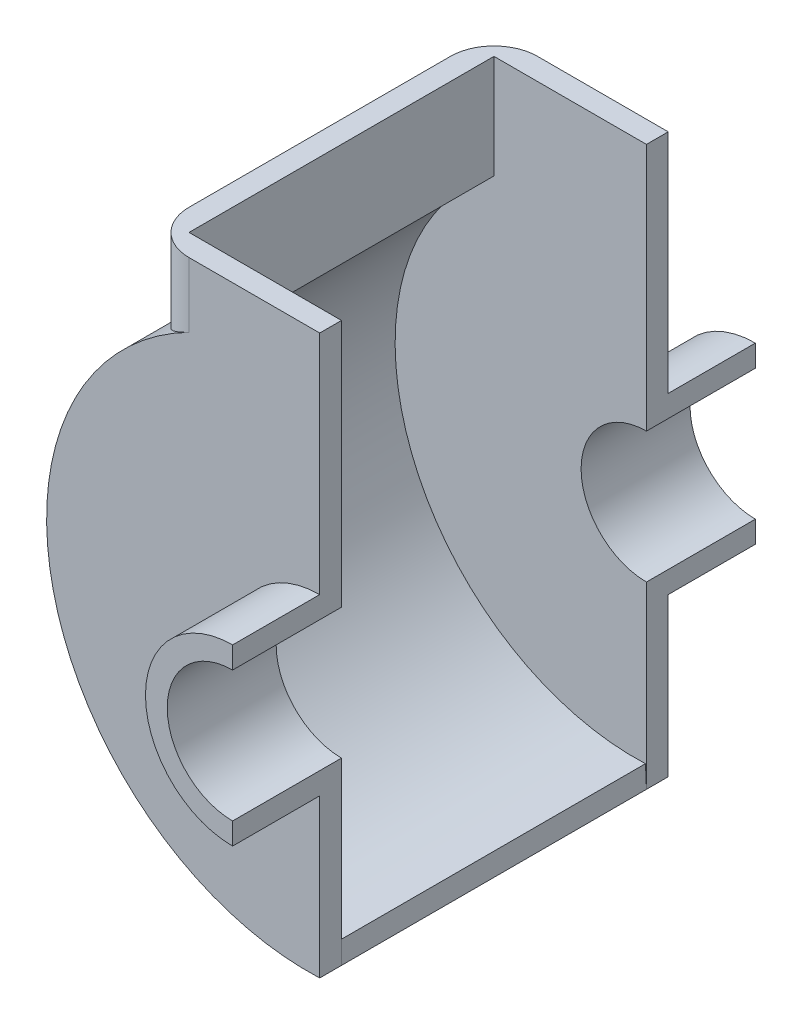
SolidWorks part; units mm, degrees
ref_plane "Płaszczyzna przednia" through (0, 0, 0) normal (0, 0, 1) x (1, 0, 0)
ref_plane "Płaszczyzna górna" through (0, 0, 0) normal (0, 1, 0) x (1, 0, 0)
ref_plane "Płaszczyzna prawa" through (0, 0, 0) normal (1, 0, 0) x (0, 0, -1)
sketch "Szkic1" plane through (0, 0, 0) normal (0, 0, 1) x (1, 0, 0)
  line L0 (0, 15) -> (0, 20)
  line L1 (0, -15) -> (0, -20)
  arc A0 (0, 15) -> (0, -15) centre (0, 0) ccw
  arc A1 (0, 20) -> (0, -20) centre (0, 0) ccw
  dimension "D1" = 30
  dimension "D2" = 40
extrude "Dodanie-wyciągnięcie1" add sketch "Szkic1" along normal blind 25
sketch "Szkic2" plane through (0, 0, 0) normal (0, 0, 1) x (1, 0, 0)
  line L0 (0, 20) -> (0, 72)
  line L1 (0, 72) -> (-40, 72)
  line L2 (-40, 72) -> (-40, 50.7094)
  line L3 (0, -20) -> (0, -56.2205)
  line L6 (0, 15) -> (0, 20)
  line L7 (0, -20) -> (0, -15)
  line L8 (0, 15) -> (0, 20)
  line L9 (0, -20) -> (0, -15)
  arc A0 (-40, 50.7094) -> (0, -56.2205) centre (-2.6916, 3.7191) ccw
  arc A3 (0, 15) -> (0, -15) centre (0, 0) ccw
  arc A4 (0, 20) -> (0, -20) centre (0, 0) ccw
  arc A5 (0, 15) -> (0, -15) centre (0, 0) ccw
  point P11 (0, 0)
  point P12 (0, 0)
  point P13 (0, 0)
  point P14 (0, 0)
  point P15 (0, 0)
  dimension "D3" = 60
  dimension "D1" = 52
  dimension "D2" = 40
  dimension "D4" = 0
extrude "Dodanie-wyciągnięcie2" add sketch "Szkic2" along normal blind 5
ref_plane "Płaszczyzna7" through (0, 0, -35) normal (0, 0, -1) x (-1, 0, 0)
mirror "Lustro4" about plane through (0, 0, -35) normal (0, 0, -1) of bodies 102
sketch "Szkic14" plane through (0, 0, 0) normal (0, 0, -1) x (-1, 0, 0)
  line L0 (40, 72) -> (40, 50.7094) construction
  line L1 (40, 72) -> (40, 50.7094)
  arc A0 (0, -56.2205) -> (40, 50.7094) centre (2.6916, 3.7191) ccw construction
  arc A1 (0, -56.2205) -> (40, 50.7094) centre (2.6916, 3.7191) ccw
extrude "Wyciągnięcie-cienka ścianka1" add sketch "Szkic14" along normal up to next thin
fillet "Zaokrąglenie1" radius 10 2 edges at (-40, 61.3547, -75) (-40, 61.3547, 5)
